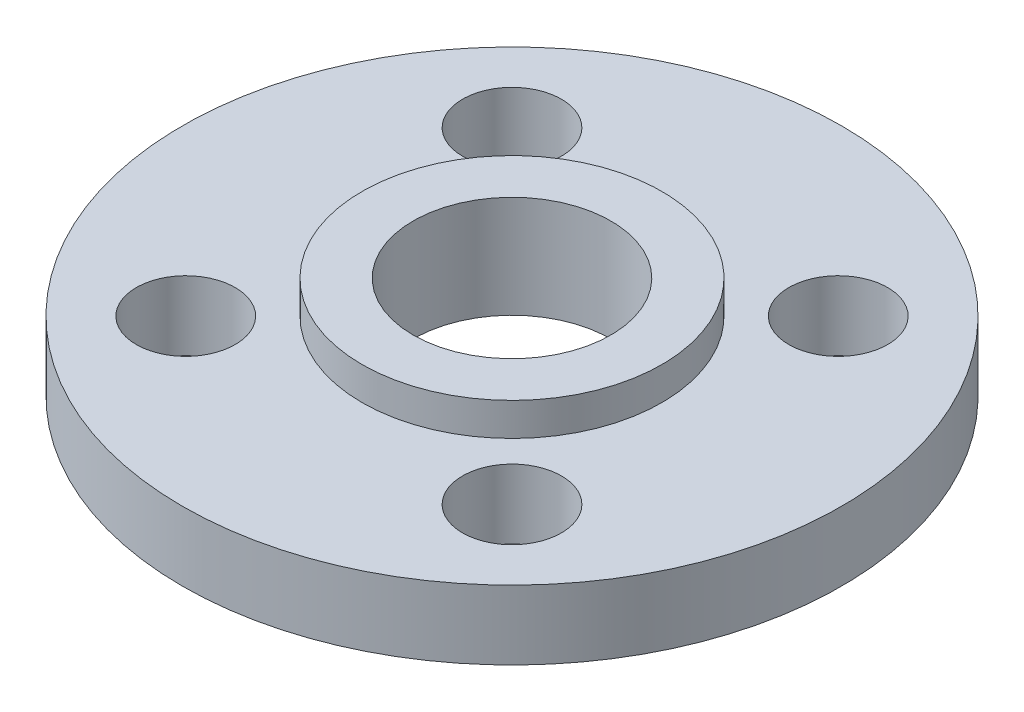
SolidWorks part; units mm, degrees
ref_plane "Plan de face" through (0, 0, 0) normal (0, 0, 1) x (1, 0, 0)
ref_plane "Plan de dessus" through (0, 0, 0) normal (0, 1, 0) x (1, 0, 0)
ref_plane "Plan de droite" through (0, 0, 0) normal (1, 0, 0) x (0, 0, -1)
sketch "Esquisse1" plane through (0, 0, 0) normal (0, 1, 0) x (1, 0, 0)
  line L1 (-4.9497, -4.9497) -> (4.9497, -4.9497) construction
  line L2 (-4.9497, -4.9497) -> (-4.9497, 4.9497) construction
  line L3 (-4.9497, 4.9497) -> (4.9497, 4.9497) construction
  line L4 (4.9497, -4.9497) -> (4.9497, 4.9497) construction
  circle A0 centre (0, 0) radius 10
  circle A1 centre (0, 0) radius 3
  circle A2 centre (0, 0) radius 7 construction
  circle A3 centre (-4.9497, -4.9497) radius 1.5
  circle A4 centre (-4.9497, 4.9497) radius 1.5
  circle A5 centre (4.9497, 4.9497) radius 1.5
  circle A6 centre (4.9497, -4.9497) radius 1.5
  dimension "D1" = 20
  dimension "D2" = 6
  dimension "D3" = 14
  dimension "D4" = 3
extrude "Boss.-Extru.1" add sketch "Esquisse1" along normal blind 2.1
sketch "Esquisse2" plane through (0, 2.1, 0) normal (0, 1, 0) x (1, 0, 0)
  circle A0 centre (0, 0) radius 4.55
  circle A1 centre (0, 0) radius 3
  circle A2 centre (0, 0) radius 3 construction
  dimension "D1" = 9.1
extrude "Boss.-Extru.2" add sketch "Esquisse2" along normal blind 1
